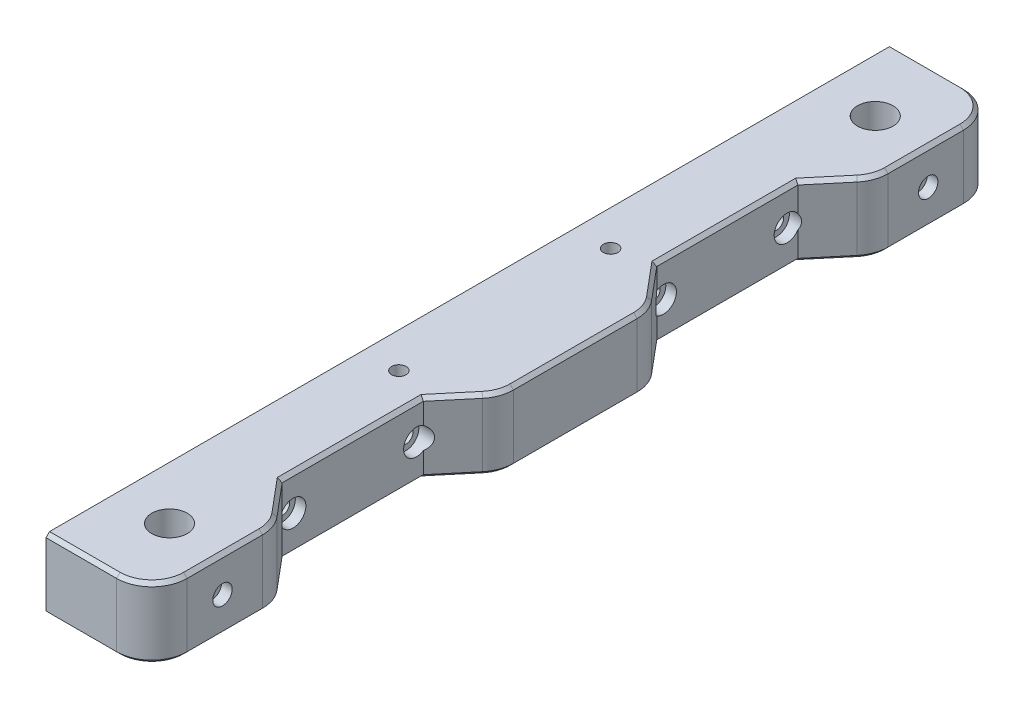
SolidWorks part; units mm, degrees
ref_plane "Front Plane" through (0, 0, 0) normal (0, 0, 1) x (1, 0, 0)
ref_plane "Top Plane" through (0, 0, 0) normal (0, 1, 0) x (1, 0, 0)
ref_plane "Right Plane" through (0, 0, 0) normal (1, 0, 0) x (0, 0, -1)
sketch "Sketch1" plane through (0, 0, 0) normal (1, 0, 0) x (0, 0, -1)
  line L1 (167.5998, 14.5216) -> (-72.4002, 14.5216)
  line L2 (167.5998, 14.5216) -> (167.5998, -5.4784)
  line L3 (167.5998, -5.4784) -> (-72.4002, -5.4784)
  line L4 (-72.4002, 14.5216) -> (-72.4002, -5.4784)
  dimension "D1" = 20
  dimension "D2" = 240
extrude "Boss-Extrude1" add sketch "Sketch1" along normal blind 30
sketch "Sketch2" plane through (0, 14.5216, 0) normal (0, 1, 0) x (1, 0, 0)
  line L0 (30, -72.4002) -> (0, -72.4002) construction
  line L1 (30, 167.5998) -> (0, 167.5998) construction
  line L2 (0, 167.5998) -> (0, -72.4002) construction
  circle A0 centre (15, 147.5998) radius 5.025
  circle A1 centre (15, -52.4002) radius 5.025
  dimension "D1" = 10.05
  dimension "D2" = 10.05
  dimension "D4" = 20
  dimension "D3" = 20
  dimension "D5" = 15
  dimension "D6" = 15
  dimension "D7" = 200
extrude "Cut-Extrude1" cut sketch "Sketch2" against normal blind 20
sketch "Sketch3" plane through (30, 0, 0) normal (1, 0, 0) x (0, 0, -1)
  line L0 (-72.4002, 14.5216) -> (-72.4002, -5.4784) construction
  line L1 (167.5998, -5.4784) -> (167.5998, 14.5216) construction
  line L2 (167.5998, 14.5216) -> (-72.4002, 14.5216) construction
  circle A0 centre (117.5998, 4.5216) radius 2.05
  circle A2 centre (-22.4002, 4.5216) radius 2.05
  circle A3 centre (12.5998, 4.5216) radius 2.05
  circle A4 centre (82.5998, 4.5216) radius 2.05
  dimension "D1" = 50
  dimension "D2" = 50
  dimension "D3" = 4.1
  dimension "D4" = 4.1
  dimension "D9" = 4.1
  dimension "D10" = 4.1
  dimension "D12" = 10
  dimension "D5" = 10
  dimension "D6" = 10
  dimension "D7" = 35
  dimension "D8" = 35
  dimension "D11" = 10
extrude "Cut-Extrude2" cut sketch "Sketch3" against normal blind 30
sketch "Sketch4" plane through (0, 14.5216, 0) normal (0, 1, 0) x (1, 0, 0)
  line L0 (0, 167.5998) -> (0, -72.4002) construction
  line L1 (22.5, 62.5998) -> (7.5, 62.5998)
  line L2 (22.5, 62.5998) -> (22.5, 32.5998)
  line L3 (22.5, 32.5998) -> (7.5, 32.5998)
  line L4 (7.5, 62.5998) -> (7.5, 32.5998)
  line L5 (30, -72.4002) -> (0, -72.4002) construction
  line L6 (30, 167.5998) -> (0, 167.5998) construction
  point P4 (22.5, 47.5998)
  dimension "D1" = 15
  dimension "D2" = 7.5
  dimension "D3" = 30
  dimension "D4" = 105
  dimension "D5" = 105
sketch "Sketch6" plane through (0, -5.4784, 0) normal (0, -1, 0) x (1, 0, 0)
  line L0 (30, 37.4002) -> (20, 25.4827)
  line L1 (30, 72.4002) -> (30, -167.5998) construction
  line L2 (20, 25.4827) -> (20, -14.5173)
  line L3 (0, 72.4002) -> (0, -167.5998) construction
  line L4 (20, -14.5173) -> (30, -26.4348)
  line L5 (30, -68.7647) -> (20, -80.6822)
  line L6 (20, -80.6822) -> (20, -120.6822)
  line L7 (20, -120.6822) -> (30, -132.5998)
  line L8 (30, -167.5998) -> (0, -167.5998) construction
  line L9 (30, -132.5998) -> (30, -68.7647)
  line L10 (30, -26.4348) -> (30, 37.4002)
  dimension "D1" = 140
  dimension "D2" = 140
  dimension "D3" = 20
  dimension "D4" = 11.9175
  dimension "D5" = 11.9175
  dimension "D6" = 40
  dimension "D7" = 35
  dimension "D8" = 140
  dimension "D9" = 140
  dimension "D10" = 20
  dimension "D11" = 11.9175
  dimension "D12" = 11.9175
  dimension "D13" = 35
  dimension "D14" = 40
extrude "Cut-Extrude5" cut sketch "Sketch6" against normal blind 32.5
fillet "Fillet1" radius 10 2 edges at (30, 4.5216, -26.4348) (30, 4.5216, -68.7647)
fillet "Fillet2" radius 10 4 edges at (30, 4.5216, 72.4002) (30, 4.5216, -167.5998) (30, 4.5216, -132.5998) (30, 4.5216, 37.4002)
chamfer "Chamfer1" distance 1 angle 45 17 edges at (10, -5.4784, 72.4002) (23.8302, -5.4784, 30.0474) (27.0711, -5.4784, 69.4713) (29.3969, -5.4784, 37.6197) (30, -5.4784, 51.7201) (10, -5.4784, -167.5998) (27.0711, -5.4784, -164.6708) (30, -5.4784, -146.9196) (23.8302, -5.4784, -125.2469) (29.3969, -5.4784, -132.8193) (20, -5.4784, -100.6822) (23.8302, -5.4784, -76.1175) (29.3969, -5.4784, -68.5452) (30, -5.4784, -47.5998) (29.3969, -5.4784, -26.6543) (23.8302, -5.4784, -19.082) (20, -5.4784, 5.4827)
chamfer "Chamfer2" distance 1 angle 45 17 edges at (20, 14.5216, -100.6822) (10, 14.5216, -167.5998) (23.8302, 14.5216, -125.2469) (27.0711, 14.5216, -164.6708) (29.3969, 14.5216, -132.8193) (30, 14.5216, -146.9196) (23.8302, 14.5216, 30.0474) (10, 14.5216, 72.4002) (29.3969, 14.5216, 37.6197) (27.0711, 14.5216, 69.4713) (30, 14.5216, 51.7201) (20, 14.5216, 5.4827) (23.8302, 14.5216, -76.1175) (23.8302, 14.5216, -19.082) (29.3969, 14.5216, -68.5452) (29.3969, 14.5216, -26.6543) (30, 14.5216, -47.5998)
sketch "Sketch10" plane through (20, 0, 0) normal (1, 0, 0) x (0, 0, -1)
  line L15 (120.6822, -4.4784) -> (120.6822, 13.5216)
  line L16 (120.6822, 13.5216) -> (80.6822, 13.5216)
  line L17 (80.6822, 13.5216) -> (80.6822, 5.2466)
  line L18 (80.6822, 3.7967) -> (80.6822, -4.4784)
  line L19 (80.6822, -4.4784) -> (120.6822, -4.4784)
  line L21 (120.6822, 13.5216) -> (80.6822, 13.5216)
  line L24 (80.6822, -4.4784) -> (120.6822, -4.4784)
  circle A0 centre (12.5998, 4.5216) radius 3.65
  arc A3 (80.6822, 3.7967) -> (80.6822, 5.2466) centre (82.5998, 4.5216) ccw
  circle A5 centre (-22.4002, 4.5216) radius 3.65
  circle A6 centre (82.5998, 4.5216) radius 3.65
  circle A7 centre (117.5998, 4.5216) radius 3.65
  dimension "D3" = 7.3
  dimension "D4" = 7.3
  dimension "D5" = 7.3
  dimension "D6" = 7.3
  dimension "D2" = 0
extrude "Cut-Extrude9" cut sketch "Sketch10" against normal blind 3 and the other way blind 3 contours A7 | A6 | A0 | A5
sketch "Sketch11" plane through (30, 0, 0) normal (1, 0, 0) x (0, 0, -1)
  line L0 (136.2395, 14.5216) -> (157.5998, 14.5216) construction
  line L1 (-62.4002, 14.5216) -> (-41.0399, 14.5216) construction
  line L2 (167.5998, 13.5216) -> (167.5998, -4.4784) construction
  line L3 (-72.4002, -4.4784) -> (-72.4002, 13.5216) construction
  circle A0 centre (147.5998, 4.5216) radius 1.5
  circle A1 centre (-52.4002, 4.5216) radius 1.5
  dimension "D1" = 3
  dimension "D2" = 3
  dimension "D3" = 10
  dimension "D4" = 10
  dimension "D5" = 20
  dimension "D6" = 20
extrude "Cut-Extrude10" cut sketch "Sketch11" against normal blind 13
sketch "Sketch12" plane through (30, 0, 0) normal (1, 0, 0) x (0, 0, -1)
  circle A0 centre (147.5998, 4.5216) radius 1.5 construction
  circle A1 centre (147.5998, 4.5216) radius 1.5
  circle A2 centre (-52.4002, 4.5216) radius 1.5 construction
  circle A3 centre (-52.4002, 4.5216) radius 1.5
  circle A4 centre (-52.4002, 4.5216) radius 2.75
  circle A5 centre (147.5998, 4.5216) radius 2.75
  dimension "D1" = 5.5
  dimension "D2" = 5.5
extrude "Cut-Extrude11" cut sketch "Sketch12" against normal blind 3
sketch "Sketch16" plane through (0, 14.5216, 0) normal (0, 1, 0) x (1, 0, 0)
  line L0 (0, 167.5998) -> (20, 167.5998) construction
  line L1 (20, -72.4002) -> (0, -72.4002) construction
  line L2 (0, 166.5998) -> (0, -71.4002) construction
  circle A0 centre (10, 77.5998) radius 2.05
  circle A1 centre (10, 17.5998) radius 2.05
  dimension "D3" = 4.1
  dimension "D4" = 4.1
  dimension "D1" = 90
  dimension "D2" = 90
  dimension "D5" = 10
  dimension "D6" = 10
extrude "Cut-Extrude12" cut sketch "Sketch16" against normal blind 40
